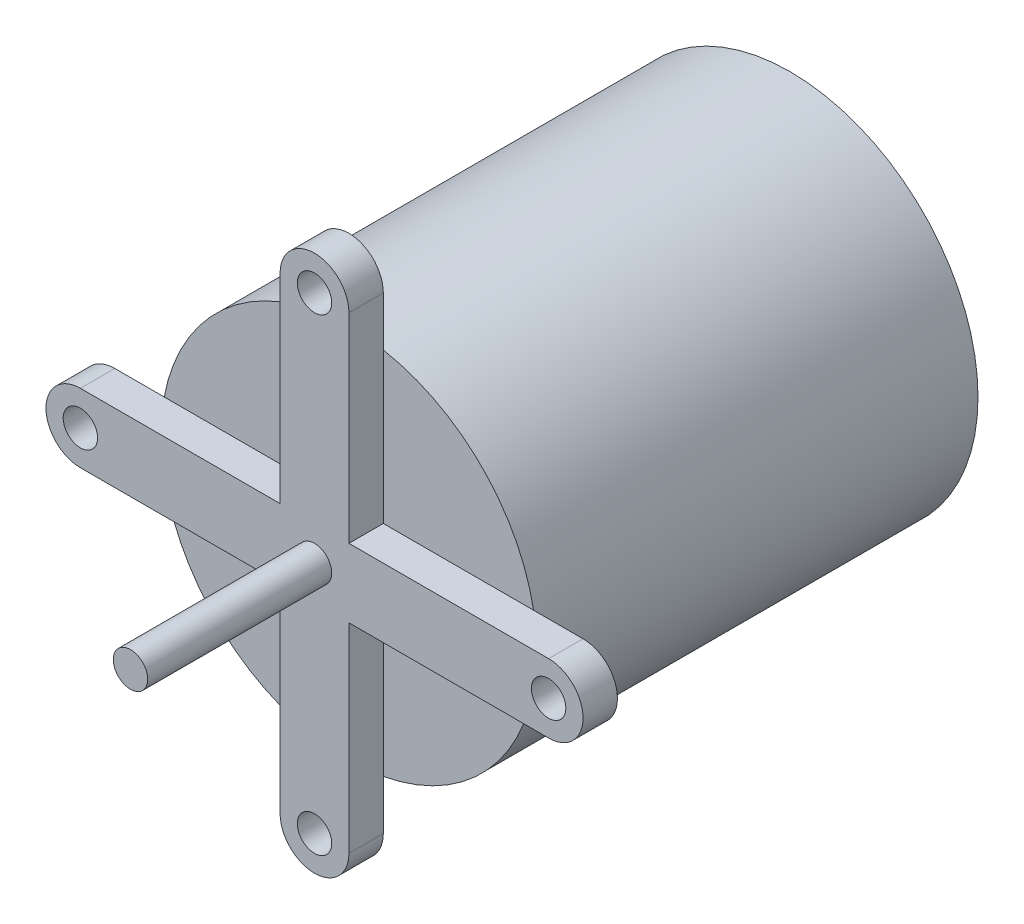
SolidWorks part; units mm, degrees
material "Motor"
ref_plane "Front Plane" through (0, 0, 0) normal (0, 0, 1) x (1, 0, 0)
ref_plane "Top Plane" through (0, 0, 0) normal (0, 1, 0) x (1, 0, 0)
ref_plane "Right Plane" through (0, 0, 0) normal (1, 0, 0) x (0, 0, -1)
sketch "Sketch1" plane through (0, 0, 0) normal (0, 0, 1) x (1, 0, 0)
  circle A0 centre (0, 0) radius 10.922
extrude "Boss-Extrude1" add sketch "Sketch1" along normal blind 25.654
sketch "Sketch2" plane through (0, 0, 25.654) normal (0, 0, 1) x (1, 0, 0)
  line L0 (-13.6118, -2) -> (-2, -2)
  line L1 (0, 0) -> (2, 2)
  line L2 (2, 2) -> (-2, 2)
  line L3 (-2, 2) -> (0, 0)
  line L4 (-2, 13.6118) -> (-2, 2)
  line L5 (2, 13.6118) -> (2, 2)
  line L6 (-13.6118, 2) -> (-2, 2)
  line L7 (2, -13.6118) -> (2, -2)
  line L8 (-2, -13.6118) -> (-2, -2)
  line L9 (13.6118, 2) -> (2, 2)
  line L10 (13.6118, -2) -> (2, -2)
  circle A12 centre (0, 13.6118) radius 1
  arc A15 (2, 13.6118) -> (-2, 13.6118) centre (0, 13.6118) ccw
  arc A16 (-13.6118, 2) -> (-13.6118, -2) centre (-13.6118, 0) ccw
  circle A17 centre (-13.6118, 0) radius 1
  arc A18 (-2, -13.6118) -> (2, -13.6118) centre (0, -13.6118) ccw
  circle A19 centre (0, -13.6118) radius 1
  arc A20 (13.6118, -2) -> (13.6118, 2) centre (13.6118, 0) ccw
  circle A21 centre (13.6118, 0) radius 1
  circle M23 centre (0, 0) radius 10.922
  dimension "D1" = 2
  dimension "D2" = 4
  dimension "D3" = 13.6118
sketch "Sketch3" plane through (0, 0, 25.654) normal (0, 0, 1) x (1, 0, 0)
  circle A0 centre (0, 0) radius 1
extrude "Boss-Extrude4" add sketch "Sketch2" along normal blind 2 contours L5 L4 L2 M23 | L5 A15 L4 A12 M23 | L10 L9 L1 L3 L6 L0 L8 L7 M23 | L10 A20 L9 A21 M23 | L2 L3 L1 | L8 A18 L7 A19 M23 | L6 A16 L0 A17 M23
extrude "Boss-Extrude3" add sketch "Sketch3" along normal blind 12.7
